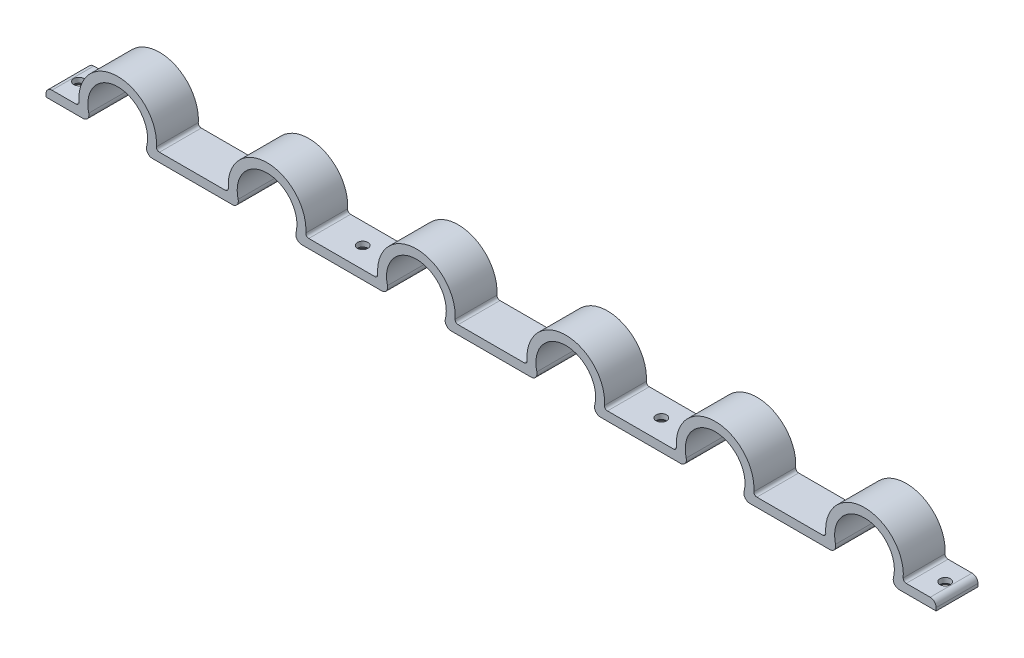
SolidWorks part; units mm, degrees
ref_plane "Plan de face" through (0, 0, 0) normal (0, 0, 1) x (1, 0, 0)
ref_plane "Plan de dessus" through (0, 0, 0) normal (0, 1, 0) x (1, 0, 0)
ref_plane "Plan de droite" through (0, 0, 0) normal (1, 0, 0) x (0, 0, -1)
sketch "Esquisse1" plane through (0, 0, 0) normal (0, 0, 1) x (1, 0, 0)
  line L0 (0, 0) -> (0, 36.4774) construction
  line L1 (-16.3397, 0) -> (16.3397, 0)
  line L2 (25, 5) -> (16.3397, 0) construction
  line L3 (16.3397, 0) -> (25, 0) construction
  line L4 (25, 0) -> (25, 5) construction
  line L5 (33.6603, 0) -> (66.3397, 0)
  line L6 (50, 0) -> (50, 34.2263) construction
  line L10 (83.6603, 0) -> (116.3397, 0)
  line L11 (100, 0) -> (100, 36.4774) construction
  line L12 (133.6603, 0) -> (149, 0)
  line L13 (-133.6603, 0) -> (-149, 0)
  line L14 (25, 0) -> (25, 5) construction
  line L19 (-83.6603, 0) -> (-116.3397, 0)
  line L20 (-33.6603, 0) -> (-66.3397, 0)
  arc A0 (16.3397, 0) -> (33.6603, 0) centre (25, 5) cw
  arc A1 (83.6603, 0) -> (66.3397, 0) centre (75, 5) ccw
  arc A2 (116.3397, 0) -> (133.6603, 0) centre (125, 5) cw
  arc A3 (-116.3397, 0) -> (-133.6603, 0) centre (-125, 5) ccw
  arc A4 (-83.6603, 0) -> (-66.3397, 0) centre (-75, 5) cw
  arc A5 (-16.3397, 0) -> (-33.6603, 0) centre (-25, 5) ccw
  dimension "D1" = 10
  dimension "D2" = 5
  dimension "D3" = 50
  dimension "D4" = 50
  dimension "D5" = 24
extrude "Extru.-Mince1" add sketch "Esquisse1" along normal blind 14 thin thin type one direction wall 3
fillet "Congé1" radius 2 12 edges at (116.3397, 0, 7) (83.6603, 0, 7) (66.3397, 0, 7) (33.6603, 0, 7) (16.3397, 0, 7) (-16.3397, 0, 7) (-116.3397, 0, 7) (-83.6603, 0, 7) (-33.6603, 0, 7) (-66.3397, 0, 7) (-133.6603, 0, 7) (133.6603, 0, 7)
fillet "Congé2" radius 1 12 edges at (137.8452, 3, 7) (112.1548, 3, 7) (87.8452, 3, 7) (62.1548, 3, 7) (37.8452, 3, 7) (12.1548, 3, 7) (-12.1548, 3, 7) (-37.8452, 3, 7) (-62.1548, 3, 7) (-87.8452, 3, 7) (-112.1548, 3, 7) (-137.8452, 3, 7)
fillet "Congé3" radius 2 2 edges at (-149, 3, 7) (149, 3, 7)
sketch "Esquisse2" plane through (0, 0, 0) normal (0, -1, 0) x (1, 0, 0)
  line L0 (-149, 7) -> (0, 7) construction
  line L1 (-149, 14) -> (-149, 0) construction
  line L2 (0, 7) -> (0, 0) construction
  line L3 (13.381, 0) -> (-13.381, 0) construction
  line L4 (0, 7) -> (0, 47.4365) construction
  line L5 (-50, 14) -> (-50, 0) construction
  line L6 (-36.619, 14) -> (-63.381, 14) construction
  line L7 (-36.619, 0) -> (-63.381, 0) construction
  line L8 (50, 14) -> (50, 0) construction
  circle A0 centre (-145, 7) radius 1.75
  circle A1 centre (145, 7) radius 1.75
  circle A3 centre (-50, 7) radius 1.75
  circle A4 centre (50, 7) radius 1.75
  dimension "D1" = 3.5
  dimension "D2" = 290
extrude "Enlèv. mat.-Extru.1" cut sketch "Esquisse2" against normal through all both and the other way through all
chamfer "Chanfrein1" distance 1.3 angle 45 4 edges at (146.75, 0, 7) (-143.25, 0, 7) (50, 0, 5.25) (-50, 0, 5.25)
